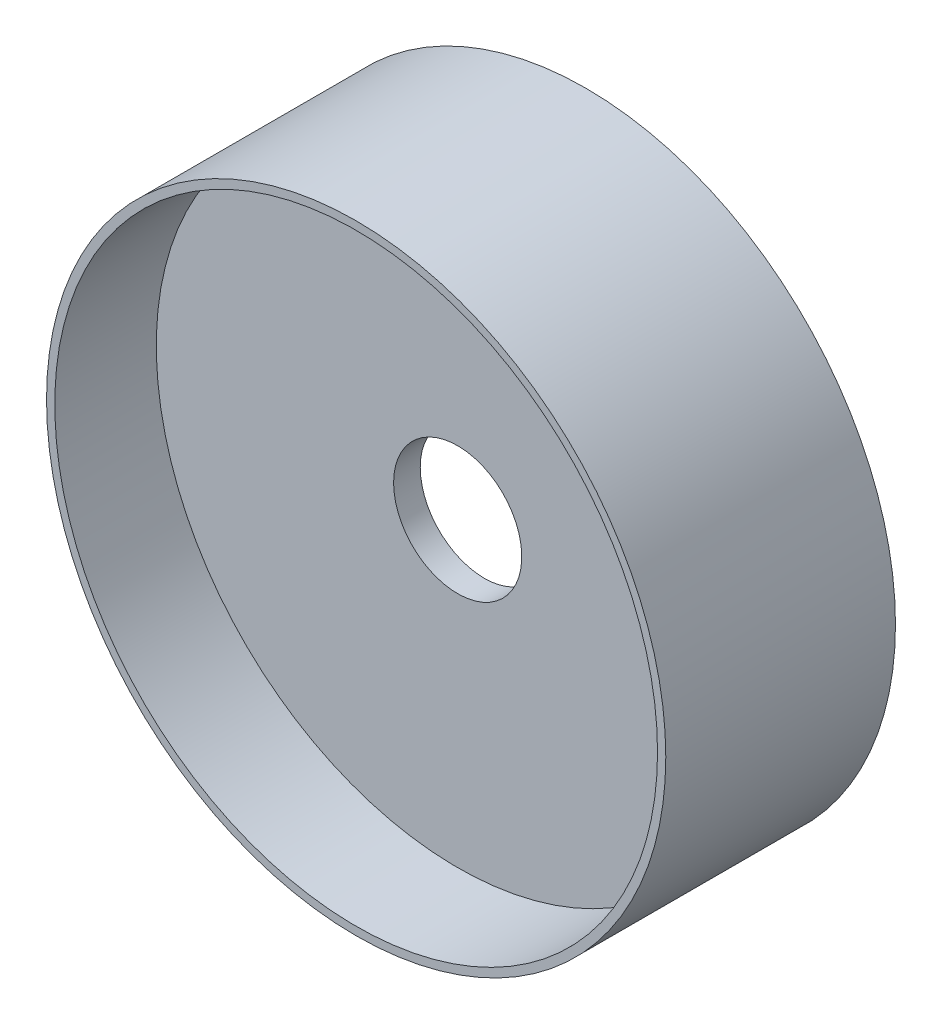
SolidWorks part; units mm, degrees
ref_plane "Front Plane" through (0, 0, 0) normal (0, 0, 1) x (1, 0, 0)
ref_plane "Top Plane" through (0, 0, 0) normal (0, 1, 0) x (1, 0, 0)
ref_plane "Right Plane" through (0, 0, 0) normal (1, 0, 0) x (0, 0, -1)
sketch "Sketch1" plane through (0, 0, 0) normal (0, 0, 1) x (1, 0, 0)
  circle A0 centre (0, 0) radius 61.976
  circle A1 centre (0, 0) radius 12.827
  dimension "D1" = 123.952
  dimension "D2" = 25.654
extrude "Boss-Extrude1" add sketch "Sketch1" along normal blind 45.974
sketch "Sketch2" plane through (0, 0, 0) normal (0, 0, 1) x (1, 0, 0)
  circle A0 centre (0, 0) radius 60.325
  dimension "D1" = 120.65
ref_plane "Plane1" through (0, 0, 22.987) normal (0, 0, 1) x (1, 0, 0)
extrude "Cut-Extrude1" cut sketch "Sketch2" along normal blind 20.32
mirror "Mirror1" about plane through (0, 0, 22.987) normal (0, 0, 1) of "Cut-Extrude1"
